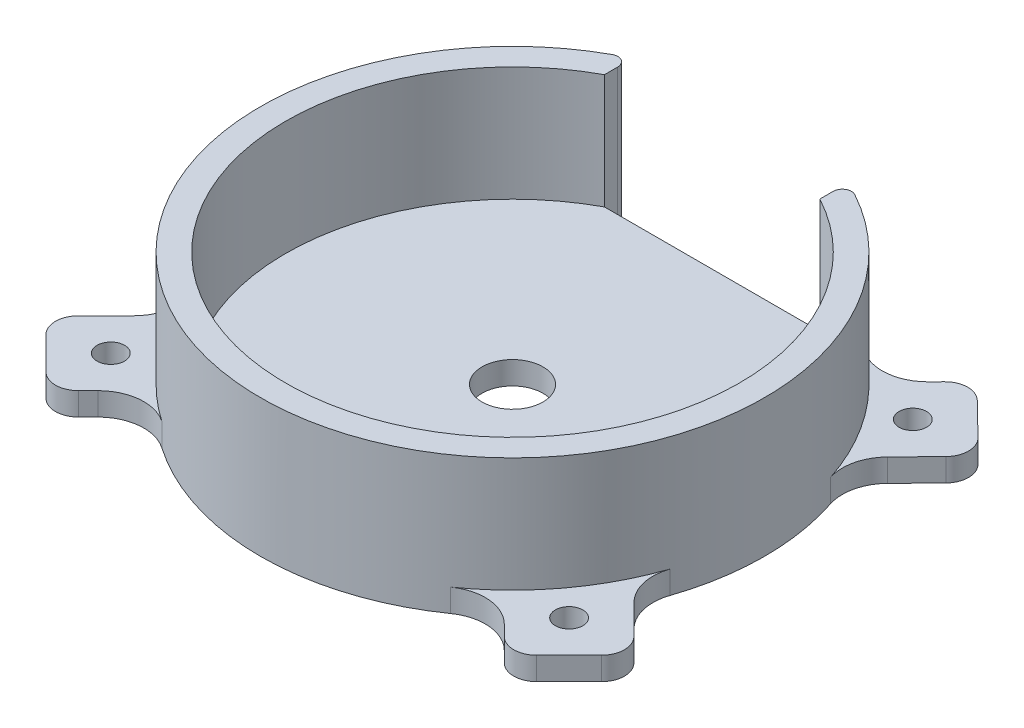
SolidWorks part; units mm, degrees
ref_plane "前视基准面" through (0, 0, 0) normal (0, 0, 1) x (1, 0, 0)
ref_plane "上视基准面" through (0, 0, 0) normal (0, 1, 0) x (1, 0, 0)
ref_plane "右视基准面" through (0, 0, 0) normal (1, 0, 0) x (0, 0, -1)
other "Configuration Table"
sketch "草图1" plane through (0, 0, 0) normal (0, 1, 0) x (1, 0, 0)
  circle A0 centre (0, 0) radius 55
  dimension "D1" = 110
extrude "凸台-拉伸1" add sketch "草图1" along normal blind 30
sketch "草图3" plane through (0, 30, 0) normal (0, 1, 0) x (1, 0, 0)
  circle A0 centre (0, 0) radius 49.5
  dimension "D1" = 99
extrude "切除-拉伸1" cut sketch "草图3" against normal blind 25
sketch "草图5" plane through (0, 30, 0) normal (0, 1, 0) x (1, 0, 0)
  line L0 (0, 0) -> (0, 49.5) construction
  line L1 (-23.5, 43.566) -> (23.5, 43.566)
  line L2 (-23.5, 43.566) -> (-23.5, 55.8089)
  line L3 (-23.5, 55.8089) -> (23.5, 55.8089)
  line L4 (23.5, 55.8089) -> (23.5, 43.566)
  circle A0 centre (0, 0) radius 49.5 construction
  circle A1 centre (0, 0) radius 49.5 construction
  dimension "D1" = 47
extrude "切除-拉伸2" cut sketch "草图5" against normal blind 30
fillet "圆角4" radius 2 1 edges at (-23.5, 15, -49.7268)
fillet "圆角5" radius 2 1 edges at (23.5, 15, -49.7268)
sketch "草图6" plane through (0, 5, 0) normal (0, 1, 0) x (1, 0, 0)
  circle A0 centre (0, 0) radius 6.65
  dimension "D1" = 13.3
extrude "切除-拉伸3" cut sketch "草图6" against normal blind 12 contours A0
sketch "草图10" plane through (0, 5, 0) normal (0, 1, 0) x (1, 0, 0)
  line L0 (-49.7204, 37.0712) -> (62.5452, 37.0712) construction
  line L1 (-49.7204, 37.0712) -> (-49.7204, -35.3765) construction
  line L2 (-49.7204, -37.9288) -> (73.1761, -37.9288) construction
  circle A0 centre (-49.7204, 37.0712) radius 3
  circle A1 centre (50.2796, 37.0712) radius 3
  circle A2 centre (-49.7204, -37.9288) radius 3
  circle A3 centre (50.2796, -37.9288) radius 3
  dimension "D1" = 6
  dimension "D2" = 6
  dimension "D4" = 6
  dimension "D6" = 6
  dimension "D3" = 100
  dimension "D5" = 75
  dimension "D7" = 100
sketch "草图14" plane through (0, 5, 0) normal (0, 1, 0) x (1, 0, 0)
  line L0 (-49.8986, 23.1329) -> (-63.8625, 37.0448)
  line L1 (-63.8625, 37.0448) -> (-49.7468, 51.2133)
  line L2 (-49.7468, 51.2133) -> (-38.1286, 39.6385)
  line L3 (49.8119, -23.319) -> (64.4217, -37.9288)
  line L4 (-49.6324, -23.6986) -> (-63.8626, -37.9288)
  line L5 (-63.8626, -37.9288) -> (-49.7204, -52.0709)
  line L6 (-49.7204, -52.0709) -> (-37.6979, -40.0484)
  line L7 (38.4757, 39.3016) -> (50.1189, 51.2124)
  line L8 (50.1189, 51.2124) -> (64.4208, 37.2319)
  line L9 (64.4208, 37.2319) -> (50.1345, 22.6171)
  line L10 (64.4217, -37.9288) -> (50.2796, -52.0709)
  line L11 (50.2796, -52.0709) -> (37.9849, -39.7762)
  arc A0 (-26.4623, 48.2156) -> (26.4623, 48.2156) centre (0, 0) ccw construction
  arc A1 (-49.6324, -23.6986) -> (-37.6979, -40.0484) centre (0, 0) ccw
  arc A2 (-49.8986, 23.1329) -> (-38.1286, 39.6385) centre (0, 0) cw
  arc A3 (38.4757, 39.3016) -> (50.1345, 22.6171) centre (0, 0) cw
  arc A4 (49.8119, -23.319) -> (37.9849, -39.7762) centre (0, 0) cw
  dimension "D1" = 10
  dimension "D2" = 10
  dimension "D3" = 10
  dimension "D4" = 10
  dimension "D5" = 10
  dimension "D6" = 10
  dimension "D7" = 10
  dimension "D8" = 10
  dimension "D9" = 10
  dimension "D10" = 10
  dimension "D11" = 10
  dimension "D12" = 10
extrude "凸台-拉伸3" add sketch "草图14" against normal up to surface (5 mm away) up to face at (0, 0, 6.65)
fillet "圆角7" radius 10 8 edges at (-49.6324, 2.5, 23.6986) (-37.6979, 2.5, 40.0484) (37.9849, 2.5, 39.7762) (49.8119, 2.5, 23.319) (50.1345, 2.5, -22.6171) (38.4757, 2.5, -39.3016) (-38.1286, 2.5, -39.6385) (-49.8986, 2.5, -23.1329)
fillet "圆角8" radius 5 8 edges at (-49.7468, 2.5, -51.2133) (-63.8625, 2.5, -37.0448) (-63.8626, 2.5, 37.9288) (-49.7204, 2.5, 52.0709) (50.2796, 2.5, 52.0709) (64.4217, 2.5, 37.9288) (64.4208, 2.5, -37.2319) (50.1189, 2.5, -51.2124)
extrude "切除-拉伸5" cut sketch "草图10" against normal up to surface (5 mm away) up to face at (0, 0, 6.65)
